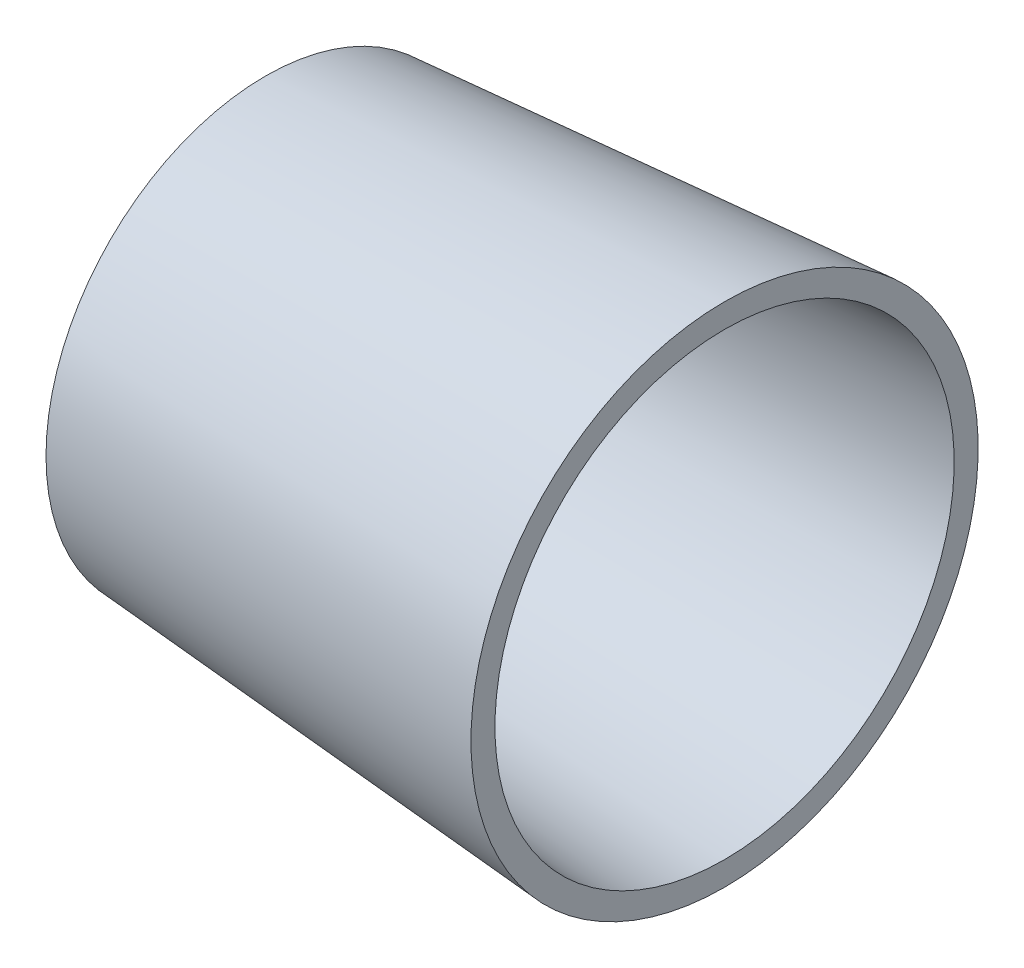
SolidWorks part; units mm, degrees
ref_plane "Front Plane" through (0, 0, 0) normal (0, 0, 1) x (1, 0, 0)
ref_plane "Top Plane" through (0, 0, 0) normal (0, 1, 0) x (1, 0, 0)
ref_plane "Right Plane" through (0, 0, 0) normal (1, 0, 0) x (0, 0, -1)
sketch "Sketch1" plane through (0, 0, 0) normal (0, 0, 1) x (1, 0, 0)
  line L0 (0, 0) -> (7000, 0) construction
  line L1 (4780, 580) -> (4780, 640)
  line L2 (4780, 640) -> (6120, 740)
  line L3 (6120, 740) -> (6120, 670)
  line L4 (6120, 670) -> (4780, 580)
revolve "Revolve1" add sketch "Sketch1" angle 360 about L0
